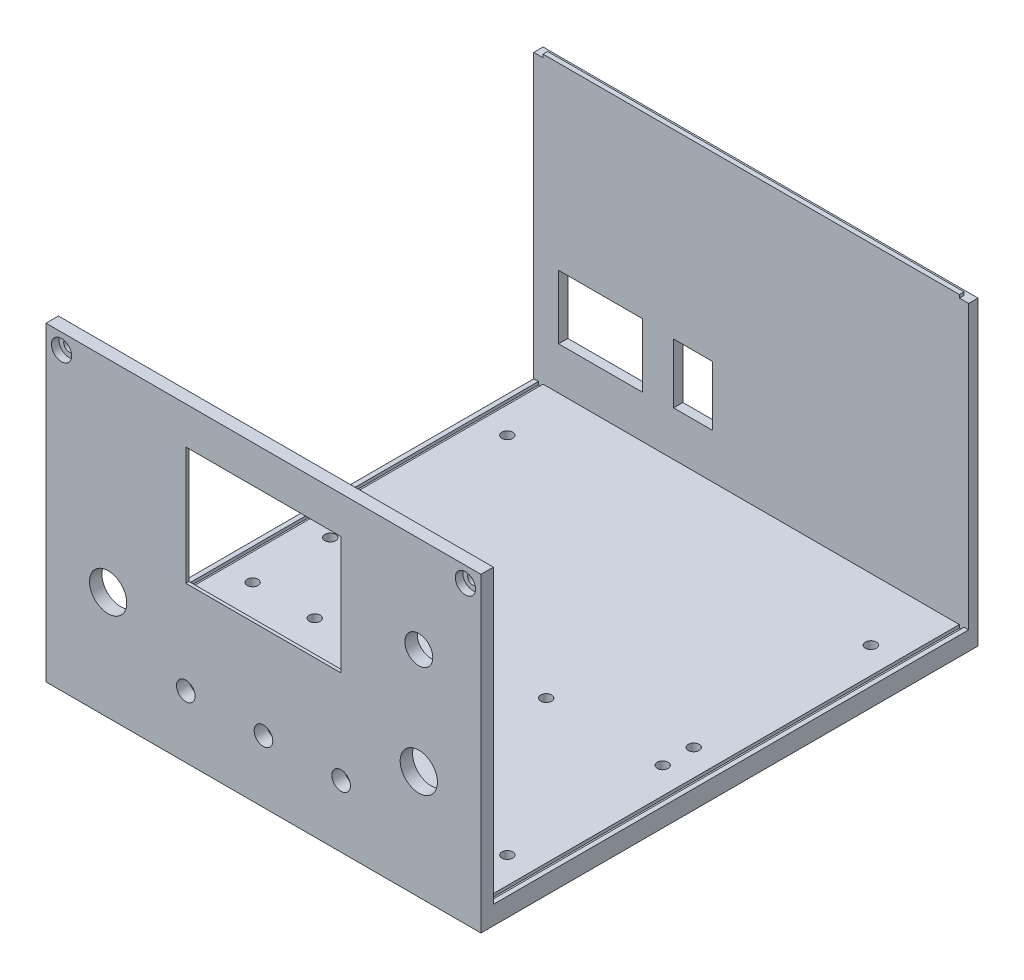
SolidWorks part; units mm, degrees
material "ABS"
ref_plane "Спереди" through (0, 0, 0) normal (0, 0, 1) x (1, 0, 0)
ref_plane "Сверху" through (0, 0, 0) normal (0, 1, 0) x (1, 0, 0)
ref_plane "Справа" through (0, 0, 0) normal (1, 0, 0) x (0, 0, -1)
sketch "Эскиз1" plane through (0, 0, 0) normal (0, 1, 0) x (1, 0, 0)
  line L1 (-70, -80) -> (70, -80)
  line L2 (-70, -80) -> (-70, 80)
  line L3 (-70, 80) -> (70, 80)
  line L4 (70, -80) -> (70, 80)
  line L5 (-70, -80) -> (70, 80) construction
  line L6 (-70, 80) -> (70, -80) construction
  point P0 (0, 0)
  dimension "D1" = 140
  dimension "D2" = 160
extrude "Бобышка-Вытянуть1" add sketch "Эскиз1" along normal blind 6
sketch "Эскиз3" plane through (0, 6, 0) normal (0, 1, 0) x (1, 0, 0)
  line L0 (70, 80) -> (-70, 80) construction
  line L1 (-70, -80) -> (70, -80)
  line L2 (-70, -80) -> (-70, 80)
  line L3 (-70, 80) -> (70, 80)
  line L4 (70, -80) -> (70, 80)
  line L5 (-70, -80) -> (70, 80) construction
  line L6 (-70, 80) -> (70, -80) construction
  line L7 (-70, -76) -> (70, -76)
  line L8 (-70, -76) -> (-70, 77)
  line L9 (-70, 77) -> (70, 77)
  line L10 (70, -76) -> (70, 77)
  line L11 (-70, -76) -> (70, 77) construction
  line L12 (-70, 77) -> (70, -76) construction
  line L14 (-70, 80) -> (-70, -80) construction
  point P0 (0, 0)
  point P7 (0, 0.5)
  line M9 (70, -80) -> (70, 80)
  line M10 (70, 80) -> (-70, 80)
  line M11 (-70, 80) -> (-70, -80)
  line M12 (-70, -80) -> (70, -80)
  dimension "D1" = 4
  dimension "D2" = 3
extrude "Бобышка-Вытянуть3" add sketch "Эскиз3" along normal blind 94 contours L7 L2 M12 M9 | L9 M11 M9 M10
sketch "Эскиз4" plane through (70, 0, 0) normal (1, 0, 0) x (0, 0, -1)
  line L0 (80, 100) -> (80, 97)
  line L1 (80, 100) -> (80, 0) construction
  line L5 (77, 100) -> (77, 6) construction
  line L7 (77, 100) -> (80, 100)
  line L8 (77, 100) -> (77, 98)
  line L9 (77, 98) -> (78.5, 98)
  line L10 (78.5, 98) -> (78.5, 97)
  line L11 (78.5, 97) -> (80, 97)
  point P11 (78.5, 100)
  dimension "D1" = 2
  dimension "D2" = 1
extrude "Вырез-Вытянуть1" cut sketch "Эскиз4" against normal through all
sketch "Эскиз5" plane through (0, 6, 0) normal (0, 1, 0) x (1, 0, 0)
  line L0 (-70, 77) -> (70, 77) construction
  line L1 (-68.5, 77) -> (68.5, 77)
  line L2 (-68.5, 77) -> (-68.5, -76)
  line L3 (-68.5, -76) -> (68.5, -76)
  line L4 (68.5, 77) -> (68.5, -76)
  line L5 (-70, -76) -> (70, -76) construction
  line L6 (-70, 77) -> (-70, -76) construction
  line L7 (-67, 77) -> (67, 77)
  line L8 (-67, 77) -> (-67, -76)
  line L9 (-67, -76) -> (67, -76)
  line L10 (67, 77) -> (67, -76)
  line L11 (70, -76) -> (70, 77) construction
  line M9 (70, 77) -> (-70, 77)
  line M11 (-70, -76) -> (70, -76)
  dimension "D1" = 1.5
  dimension "D2" = 1.5
  dimension "D3" = 1.5
  dimension "D4" = 1.5
extrude "Вырез-Вытянуть2" cut sketch "Эскиз5" against normal blind 1 contours L10 L4 M9 M11 | L8 L2 M9 M11
sketch "Эскиз6" plane through (0, 6, 0) normal (0, 1, 0) x (1, 0, 0)
  line L0 (0, -81.6579) -> (0, 74.9463) construction
  line L1 (-67, 77) -> (67, 77) construction
  line L6 (-58.5, 0) -> (58.5, 0)
  line L7 (-58.5, 0) -> (-58.5, 57)
  line L8 (-58.5, 57) -> (58.5, 57)
  line L9 (58.5, 0) -> (58.5, 57)
  line L10 (-58.5, 0) -> (58.5, 57) construction
  line L11 (-58.5, 57) -> (58.5, 0) construction
  line L12 (21, -60) -> (58.5, -60)
  line L13 (21, -60) -> (21, -10)
  line L14 (21, -10) -> (58.5, -10)
  line L15 (58.5, -60) -> (58.5, -10)
  line L16 (21, -60) -> (58.5, -10) construction
  line L17 (21, -10) -> (58.5, -60) construction
  line L18 (-18.875, -50) -> (1.125, -50)
  line L19 (-18.875, -50) -> (-18.875, -25)
  line L20 (-18.875, -25) -> (1.125, -25)
  line L21 (1.125, -50) -> (1.125, -25)
  line L22 (-18.875, -50) -> (1.125, -25) construction
  line L23 (-18.875, -25) -> (1.125, -50) construction
  line L24 (-58.5, -50) -> (-38.5, -50)
  line L25 (-58.5, -50) -> (-58.5, -25)
  line L26 (-58.5, -25) -> (-38.5, -25)
  line L27 (-38.5, -50) -> (-38.5, -25)
  line L28 (-58.5, -50) -> (-38.5, -25) construction
  line L29 (-58.5, -25) -> (-38.5, -50) construction
  point P3 (0, 28.5)
  point P9 (-8.875, -37.5)
  point P10 (39.75, -35)
  point P19 (-48.5, -37.5)
  dimension "D1" = 57
  dimension "D2" = 117
  dimension "D3" = 50
  dimension "D4" = 37.5
  dimension "D5" = 25
  dimension "D6" = 20
  dimension "D7" = 10
  dimension "D8" = 19.625
  dimension "D9" = 20
  dimension "D10" = 10
hole_wizard "Отверстие с зазором M21" positions "Эскиз7" profile "Эскиз8" hole size "M2" standard "ISO"
sketch "Эскиз7" plane through (0, 6, 0) normal (0, 1, 0) x (1, 0, 0)
  point P0 (-58.5, -25)
  point P3 (-38.5, -25)
  point P6 (-38.5, -50)
  point P9 (-58.5, -50)
  point P12 (-18.875, -25)
  point P15 (1.125, -25)
  point P18 (-18.875, -50)
  point P21 (1.125, -50)
  point P24 (21, -10)
  point P27 (21, -60)
  point P30 (58.5, -60)
  point P33 (58.5, -10)
  point P36 (-58.5, 57)
  point P39 (-58.5, 0)
  point P42 (58.5, 0)
  point P45 (58.5, 57)
sketch "Эскиз8" plane through (-58.5, 6, 25) normal (1, 0, 0) x (0, 0, 1)
  line L0 (0, 0) -> (0, 3)
  line L1 (0, 3) -> (1.75, 3)
  line L2 (1.75, 3) -> (1.75, 0)
  line L5 (1.75, 0) -> (0, 0)
  line L10 (0, 3) -> (-1.75, 3) construction
  line L11 (0, -6.35) -> (0, 107.95) construction
  dimension "Диаметр отверстия" = 3.5
  dimension "Глубина отверстия" = 3
  dimension "Угол заточки сверла" = 180
sketch "Эскиз9" plane through (0, 0, 80) normal (0, 0, 1) x (1, 0, 0)
  line L0 (0, -7.6249) -> (0, 107.1928) construction
  line L1 (-25, 50) -> (25, 50)
  line L2 (-25, 50) -> (-25, 88)
  line L3 (-25, 88) -> (25, 88)
  line L4 (25, 50) -> (25, 88)
  line L5 (-25, 50) -> (25, 88) construction
  line L6 (-25, 88) -> (25, 50) construction
  line L7 (-25, 20) -> (0, 20) construction
  line L8 (-70, 100) -> (70, 100) construction
  circle A0 centre (-25, 20) radius 3
  circle A1 centre (0, 20) radius 3
  circle A2 centre (25, 20) radius 3
  circle A3 centre (50, 69) radius 4.5
  circle A4 centre (50, 35) radius 6
  circle A5 centre (-50, 35) radius 6
  point P0 (0, 69)
  dimension "D4" = 25
  dimension "D5" = 3
  dimension "D6" = 6
  dimension "D7" = 12
  dimension "D1" = 50
  dimension "D2" = 38
  dimension "D8" = 25
  dimension "D9" = 15
  dimension "D10" = 12
  dimension "D11" = 30
extrude "Вырез-Вытянуть3" cut sketch "Эскиз9" against normal up to next
sketch "Эскиз10" plane through (0, 0, 76) normal (0, 0, -1) x (-1, 0, 0)
  line L0 (-25, 88) -> (25, 88) construction
  line L1 (-25, 45) -> (29, 45)
  line L2 (-25, 45) -> (-25, 93)
  line L3 (-25, 93) -> (29, 93)
  line L4 (29, 45) -> (29, 93)
  line L5 (-25, 45) -> (29, 93) construction
  line L6 (-25, 93) -> (29, 45) construction
  line L7 (25, 50) -> (-25, 50) construction
  line L8 (-25, 50) -> (-25, 88) construction
  line L10 (25, 88) -> (25, 50) construction
  point P0 (1.2171, 68.304)
  dimension "D1" = 5
  dimension "D2" = 5
  dimension "D3" = 4
extrude "Вырез-Вытянуть4" cut sketch "Эскиз10" against normal blind 3
sketch "Эскиз11" plane through (0, 0, 76) normal (0, 0, -1) x (-1, 0, 0)
  line L0 (-1.25, 25.8683) -> (1.25, 25.8683)
  line L1 (-26.25, 25.8683) -> (-23.75, 25.8683)
  line L2 (-26.25, 25.8683) -> (-26.25, 27.3683)
  line L3 (-26.25, 27.3683) -> (-23.75, 27.3683)
  line L4 (-23.75, 25.8683) -> (-23.75, 27.3683)
  line L5 (-26.25, 25.8683) -> (-23.75, 27.3683) construction
  line L6 (-26.25, 27.3683) -> (-23.75, 25.8683) construction
  line L7 (-1.25, 25.8683) -> (-1.25, 27.3683)
  line L8 (-1.25, 27.3683) -> (1.25, 27.3683)
  line L9 (1.25, 25.8683) -> (1.25, 27.3683)
  line L10 (-1.25, 25.8683) -> (1.25, 27.3683) construction
  line L11 (-1.25, 27.3683) -> (1.25, 25.8683) construction
  line L12 (23.75, 25.8683) -> (26.25, 25.8683)
  line L13 (23.75, 25.8683) -> (23.75, 27.3683)
  line L14 (23.75, 27.3683) -> (26.25, 27.3683)
  line L15 (26.25, 25.8683) -> (26.25, 27.3683)
  line L16 (23.75, 25.8683) -> (26.25, 27.3683) construction
  line L17 (23.75, 27.3683) -> (26.25, 25.8683) construction
  line L18 (-50, 64.5) -> (-60.1065, 64.5) construction
  line L19 (-51.5, 77.5) -> (-48.5, 77.5)
  line L20 (-51.5, 77.5) -> (-51.5, 79.5)
  line L21 (-51.5, 79.5) -> (-48.5, 79.5)
  line L22 (-48.5, 77.5) -> (-48.5, 79.5)
  line L23 (-51.5, 77.5) -> (-48.5, 79.5) construction
  line L24 (-51.5, 79.5) -> (-48.5, 77.5) construction
  circle A5 centre (-25, 20) radius 6 construction
  circle A6 centre (-50, 69) radius 4.5 construction
  point P0 (-25, 26.6183)
  point P5 (-50, 78.5)
  point P9 (0, 26.6183)
  point P10 (-25, 20)
  point P16 (25, 26.6183)
  point P28 (-50, 69)
  dimension "D3" = 12
  dimension "D1" = 2.5
  dimension "D2" = 1.5
  dimension "D4" = 3
  dimension "D5" = 2
  dimension "D6" = 3
  dimension "D7" = 15
extrude "Вырез-Вытянуть5" cut sketch "Эскиз11" against normal blind 2.5
sketch "Эскиз12" plane through (0, 0, 80) normal (0, 0, 1) x (1, 0, 0)
  line L0 (-70, 100) -> (-70, 0) construction
  line L1 (-70, 100) -> (70, 100) construction
  line L2 (70, 100) -> (70, 0) construction
  point P0 (-65, 95)
  point P1 (65, 95)
  dimension "D1" = 5
  dimension "D2" = 5
  dimension "D3" = 5
hole_wizard "Цековка для винта с внутренним шестигранником с тонкой головкой M31" positions "Эскиз13" profile "Эскиз14" counterbore size "M3" standard "DIN"
sketch "Эскиз13" plane through (0, 0, 80) normal (0, 0, 1) x (1, 0, 0)
  point P0 (-65, 95)
  point P3 (65, 95)
sketch "Эскиз14" plane through (-65, 95, 80) normal (1, 0, 0) x (0, -1, 0)
  line L0 (0, 0) -> (0, 4)
  line L1 (0, 4) -> (1.7, 4)
  line L3 (1.7, 4) -> (1.7, 2.4)
  line L4 (1.7, 2.4) -> (3.25, 2.4)
  line L5 (3.25, 2.4) -> (3.25, 0)
  line L7 (3.25, 0) -> (0, 0)
  line L11 (0, -6.35) -> (0, 107.95) construction
  dimension "Диаметр сквозного отверстия" = 3.4
  dimension "Глубина сквозного отверстия" = 4
  dimension "Диаметр цековки" = 6.5
  dimension "Глубина цековки" = 2.4
sketch "Эскиз15" plane through (0, 0, -80) normal (0, 0, -1) x (-1, 0, 0)
  line L1 (12.5, 20.4) -> (25, 20.4)
  line L2 (12.5, 20.4) -> (12.5, 39.6)
  line L3 (12.5, 39.6) -> (25, 39.6)
  line L4 (25, 20.4) -> (25, 39.6)
  line L5 (12.5, 20.4) -> (25, 39.6) construction
  line L6 (12.5, 39.6) -> (25, 20.4) construction
  line L7 (-70, 0) -> (70, 0) construction
  line L9 (35, 19.75) -> (62, 19.75)
  line L10 (35, 19.75) -> (35, 40.25)
  line L11 (35, 40.25) -> (62, 40.25)
  line L12 (62, 19.75) -> (62, 40.25)
  line L13 (35, 19.75) -> (62, 40.25) construction
  line L14 (35, 40.25) -> (62, 19.75) construction
  line L15 (70, 97) -> (70, 0) construction
  point P0 (18.75, 30)
  point P5 (48.5, 30)
  dimension "D1" = 12.5
  dimension "D2" = 19.2
  dimension "D3" = 30
  dimension "D4" = 27
  dimension "D5" = 20.5
  dimension "D6" = 10
  dimension "D7" = 8
extrude "Вырез-Вытянуть6" cut sketch "Эскиз15" against normal up to next
hole_wizard "Отверстие с зазором M22" positions "Эскиз19" profile "Эскиз20" hole size "M2" standard "ISO"
sketch "Эскиз19" plane through (0, 3, 0) normal (0, 1, 0) x (1, 0, 0)
  point P0 (-58.5, -50)
  point P3 (-38.5, -50)
  point P6 (-18.875, -50)
  point P9 (1.125, -50)
  point P12 (1.125, -25)
  point P15 (-18.875, -25)
  point P18 (-38.5, -25)
  point P21 (-58.5, -25)
  point P24 (21, -10)
  point P27 (21, -60)
  point P30 (58.5, -60)
  point P33 (58.5, -10)
  point P36 (58.5, 0)
  point P39 (-58.5, 0)
  point P42 (58.5, 57)
  point P45 (-58.5, 57)
sketch "Эскиз20" plane through (-58.5, 3, 50) normal (1, 0, 0) x (0, 0, 1)
  line L0 (0, 0) -> (0, 1)
  line L1 (0, 1) -> (1.1, 1)
  line L2 (1.1, 1) -> (1.1, 0)
  line L5 (1.1, 0) -> (0, 0)
  line L10 (0, 1) -> (-1.1, 1) construction
  line L11 (0, -6.35) -> (0, 107.95) construction
  dimension "Диаметр отверстия" = 2.2
  dimension "Глубина отверстия" = 1
  dimension "Угол заточки сверла" = 180
sketch "Эскиз21" plane through (0, 0, 76) normal (0, 0, -1) x (-1, 0, 0)
  point P0 (32.35, 86)
  point P1 (32.35, 51.75)
  point P3 (-28.9, 86)
  point P5 (-28.9, 51.75)
hole_wizard "Отверстие с зазором M23" positions "Эскиз22" profile "Эскиз23" hole size "M2" standard "ISO"
sketch "Эскиз22" plane through (0, 0, 76) normal (0, 0, -1) x (-1, 0, 0)
  point P0 (-28.9, 86)
  point P3 (-28.9, 51.75)
  point P6 (32.35, 86)
  point P9 (32.35, 51.75)
sketch "Эскиз23" plane through (28.9, 86, 76) normal (1, 0, 0) x (0, 1, 0)
  line L0 (0, 0) -> (0, 3)
  line L1 (0, 3) -> (1.75, 3)
  line L2 (1.75, 3) -> (1.75, 0)
  line L5 (1.75, 0) -> (0, 0)
  line L10 (0, 3) -> (-1.75, 3) construction
  line L11 (0, -6.35) -> (0, 107.95) construction
  dimension "Диаметр отверстия" = 3.5
  dimension "Глубина отверстия" = 3
  dimension "Угол заточки сверла" = 180
sketch "Эскиз24" plane through (0, 0, -78.5) normal (0, 0, -1) x (-1, 0, 0)
  line L0 (70, 98) -> (-70, 98) construction
  line L1 (-70, 97) -> (-67, 97)
  line L2 (-70, 97) -> (-70, 98)
  line L3 (-70, 98) -> (-67, 98)
  line L4 (-67, 97) -> (-67, 98)
  line L6 (70, 97) -> (67, 97)
  line L7 (70, 97) -> (70, 98)
  line L8 (70, 98) -> (67, 98)
  line L9 (67, 97) -> (67, 98)
  dimension "D1" = 3
  dimension "D2" = 3
extrude "Вырез-Вытянуть7" cut sketch "Эскиз24" against normal up to next
